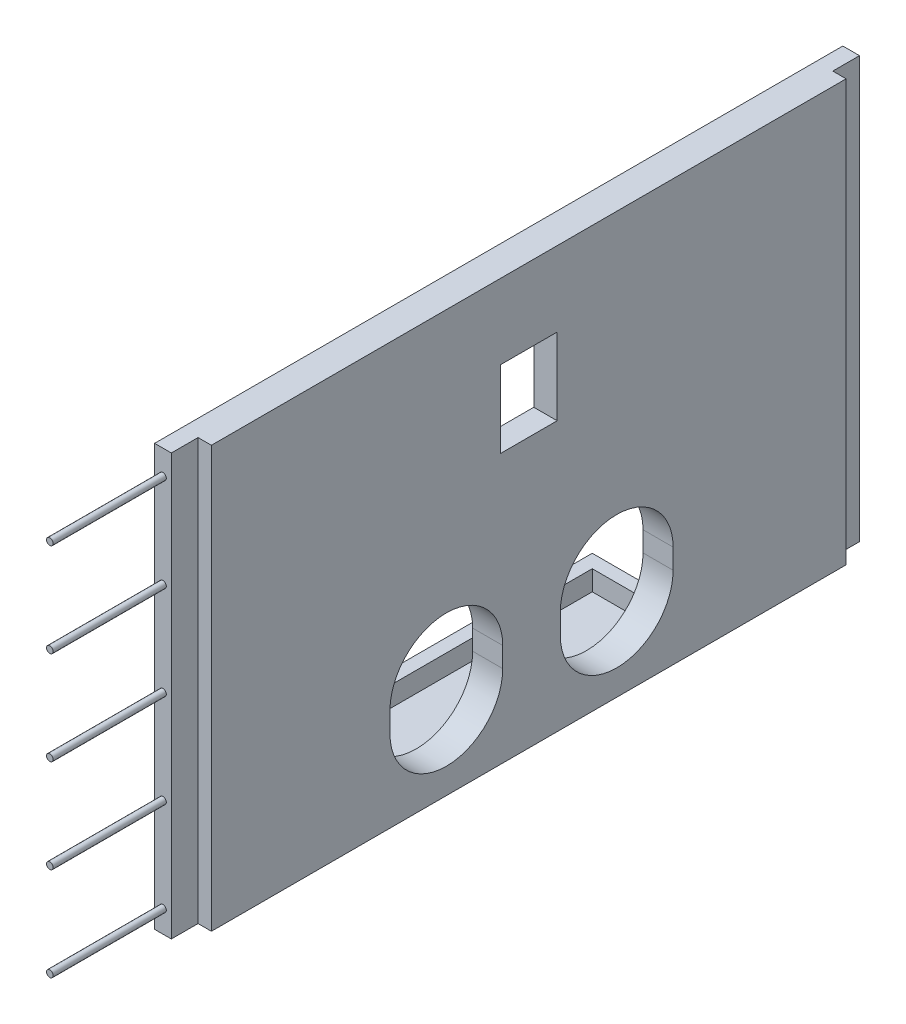
SolidWorks part; units mm, degrees
ref_plane "정면" through (0, 0, 0) normal (0, 0, 1) x (1, 0, 0)
ref_plane "윗면" through (0, 0, 0) normal (0, 1, 0) x (1, 0, 0)
ref_plane "우측면" through (0, 0, 0) normal (1, 0, 0) x (0, 0, -1)
sketch "스케치1" plane through (0, 0, 0) normal (0, 1, 0) x (1, 0, 0)
  line L0 (-2.25, 51.5) -> (0.25, 51.5)
  line L1 (-2.25, 51.5) -> (-2.25, -51.5)
  line L2 (-2.25, -51.5) -> (0.25, -51.5)
  line L3 (0.25, 51.5) -> (0.25, -51.5)
  line L4 (0.25, 47.5) -> (2.25, 47.5)
  line L5 (0.25, 47.5) -> (0.25, -47.5)
  line L6 (0.25, -47.5) -> (2.25, -47.5)
  line L7 (2.25, 47.5) -> (2.25, -47.5)
  dimension "D1" = 2.5
  dimension "D2" = 4
extrude "보스-돌출1" add sketch "스케치1" along normal blind 63 contours L3 L0 L1 L2 | L7 L4 L3 L6
sketch "스케치2" plane through (-2.25, 0, 0) normal (-1, 0, 0) x (0, 0, 1)
  line L0 (-51.5, 0) -> (51.5, 0) construction
  line L1 (-22.5, 22.5) -> (22.5, 22.5)
  line L2 (-22.5, 22.5) -> (-22.5, 2)
  line L3 (-22.5, 2) -> (22.5, 2)
  line L4 (22.5, 22.5) -> (22.5, 2)
  line L5 (51.5, 63) -> (51.5, 0) construction
  dimension "D1" = 45
  dimension "D2" = 20.5
  dimension "D3" = 2
  dimension "D4" = 29
sketch "스케치5" plane through (-2.25, 0, 0) normal (-1, 0, 0) x (0, 0, 1)
  line L1 (-25, 2) -> (25, 2)
  line L2 (-25, 2) -> (-25, 0)
  line L3 (-25, 0) -> (25, 0)
  line L4 (25, 2) -> (25, 0)
  line L5 (-51.5, 63) -> (-51.5, 0) construction
  dimension "D1" = 26.5
  dimension "D2" = 50
extrude "보스-돌출2" add sketch "스케치5" along normal blind 11
sketch "스케치7" plane through (0, 2, 0) normal (0, 1, 0) x (1, 0, 0)
  line L0 (-2.25, 23) -> (-11.25, 23)
  line L1 (-11.25, 23) -> (-11.25, -23)
  line L2 (-11.25, -23) -> (-2.25, -23)
  line L3 (-2.25, 23) -> (-2.25, 25)
  line L4 (-2.25, -25) -> (-2.25, 25)
  line L5 (-2.25, 25) -> (-13.25, 25)
  line L6 (-13.25, 25) -> (-13.25, -25)
  line L7 (-13.25, -25) -> (-2.25, -25)
  line L8 (-2.25, -25) -> (-2.25, -23)
  line L9 (-2.25, 25) -> (-13.25, 25)
  line L10 (-13.25, 25) -> (-13.25, -25)
  line L11 (-13.25, -25) -> (-2.25, -25)
  dimension "D1" = 0
  dimension "D2" = 2
extrude "보스-돌출3" add sketch "스케치7" along normal blind 3
sketch "스케치9" plane through (0, 2, 0) normal (0, 1, 0) x (1, 0, 0)
  line L0 (-11.25, -23) -> (-11.25, 23) construction
  line L1 (-10.75, 22.5) -> (-9, 22.5)
  line L2 (-10.75, 22.5) -> (-10.75, -22.5)
  line L3 (-10.75, -22.5) -> (-9, -22.5)
  line L4 (-9, 22.5) -> (-9, -22.5)
  line L5 (-2.25, -23) -> (-11.25, -23) construction
  dimension "D1" = 45
  dimension "D2" = 1.75
  dimension "D3" = 0.5
  dimension "D4" = 0.5
sketch "스케치10" plane through (2.25, 0, 0) normal (1, 0, 0) x (0, 0, -1)
  line L0 (-12.34, 12.25) -> (-12.34, 15.25) construction
  line L1 (13.16, 12.25) -> (13.16, 15.25) construction
  line L2 (-20.78, 15.25) -> (-20.78, 12.25)
  line L3 (-3.9, 15.25) -> (-3.9, 12.25)
  line L4 (4.72, 15.25) -> (4.72, 12.25)
  line L5 (21.6, 15.25) -> (21.6, 12.25)
  arc A0 (-20.78, 12.25) -> (-3.9, 12.25) centre (-12.34, 12.25) ccw
  arc A1 (4.72, 12.25) -> (21.6, 12.25) centre (13.16, 12.25) ccw
  arc A2 (-3.9, 15.25) -> (-20.78, 15.25) centre (-12.34, 15.25) ccw
  arc A3 (21.6, 15.25) -> (4.72, 15.25) centre (13.16, 15.25) ccw
  dimension "D1" = 16.88
  dimension "D2" = 16.88
  dimension "D4" = 16.88
  dimension "D5" = 16.88
  dimension "D3" = 3
extrude "컷-돌출1" cut sketch "스케치10" against normal up to surface (4.5 mm away) up to face at (-2.25, 12.5, 0)
sketch "스케치11" plane through (-2.25, 0, 0) normal (-1, 0, 0) x (0, 0, 1)
  line L0 (-51.5, 63) -> (-51.5, 0) construction
  line L1 (-12.5, 57) -> (12.5, 57)
  line L2 (-12.5, 57) -> (-12.5, 30)
  line L3 (-12.5, 30) -> (12.5, 30)
  line L4 (12.5, 57) -> (12.5, 30)
  line L7 (-4.25, 51.8) -> (4.25, 51.8)
  line L8 (-4.25, 51.8) -> (-4.25, 40.3)
  line L9 (-4.25, 40.3) -> (4.25, 40.3)
  line L10 (4.25, 51.8) -> (4.25, 40.3)
  dimension "D1" = 25
  dimension "D2" = 27
  dimension "D3" = 39
  dimension "D5" = 8.25
  dimension "D7" = 11.5
  dimension "D8" = 8.5
extrude "컷-돌출2" cut sketch "스케치11" against normal up to surface (4.5 mm away) contours L10 L7 L8 L9 up to face at (2.25, 13.75, 12.34)
sketch "스케치12" plane through (-2.25, 0, 0) normal (-1, 0, 0) x (0, 0, 1)
  line L0 (-13, 57.5) -> (-13, 29.5)
  line L1 (-12.5, 57) -> (12.5, 57)
  line L2 (-12.5, 57) -> (-12.5, 30)
  line L3 (-12.5, 30) -> (12.5, 30)
  line L4 (12.5, 57) -> (12.5, 30)
  line L5 (-13, 29.5) -> (13, 29.5)
  line L6 (13, 57.5) -> (13, 29.5)
  line L7 (-13, 57.5) -> (13, 57.5)
  line M21 (4.25, 51.8) -> (4.25, 40.3)
  line M22 (4.25, 40.3) -> (-4.25, 40.3)
  line M23 (-4.25, 40.3) -> (-4.25, 51.8)
  line M24 (-4.25, 51.8) -> (4.25, 51.8)
  dimension "D1" = 0.5
extrude "컷-돌출3" cut sketch "스케치12" against normal blind 1 contours L4 L1 L2 L3 M24 M21 M22 M23 | L7 L0 L5 L6 L1 L4 L3 L2
sketch "스케치13" plane through (-2.25, 0, 0) normal (-1, 0, 0) x (0, 0, 1)
  line L0 (-51.5, 63) -> (-51.5, 0) construction
  line L1 (-15, 29.5) -> (15, 29.5)
  line L2 (-15, 29.5) -> (-15, 27.5)
  line L3 (-15, 27.5) -> (15, 27.5)
  line L4 (15, 29.5) -> (15, 27.5)
  line L6 (-13, 29.5) -> (13, 29.5) construction
  dimension "D1" = 36.5
  dimension "D2" = 30
  dimension "D3" = 2
extrude "보스-돌출4" add sketch "스케치13" along normal blind 4
sketch "스케치14" plane through (0, 29.5, 0) normal (0, 1, 0) x (1, 0, 0)
  line L0 (-2.25, -13) -> (-2.25, -15)
  line L1 (-6.25, 15) -> (-2.25, 15)
  line L2 (-6.25, 15) -> (-6.25, -15)
  line L3 (-6.25, -15) -> (-2.25, -15)
  line L4 (-2.25, 15) -> (-2.25, 13)
  line L5 (-4.25, 13) -> (-2.25, 13)
  line L6 (-4.25, 13) -> (-4.25, -13)
  line L7 (-4.25, -13) -> (-2.25, -13)
  dimension "D1" = 2
  dimension "D2" = 2
  dimension "D3" = 2
  dimension "D4" = 2
extrude "보스-돌출5" add sketch "스케치14" along normal blind 3
sketch "스케치15" plane through (0, 0, 51.5) normal (0, 0, 1) x (1, 0, 0)
  line L1 (-2.25, 63) -> (-2.25, 0) construction
  circle A0 centre (-1, 3.3469) radius 0.5
  circle A1 centre (-1, 17.3469) radius 0.5
  circle A2 centre (-1, 31.3469) radius 0.5
  circle A3 centre (-1, 45.3469) radius 0.5
  circle A4 centre (-1, 59.3469) radius 0.5
  dimension "D1" = 1
  dimension "D2" = 1.25
  dimension "D3" = 5
extrude "보스-돌출6" add sketch "스케치15" along normal up to surface (16.9333 mm away) contours A0 | A1 | A2 | A3 | A4
